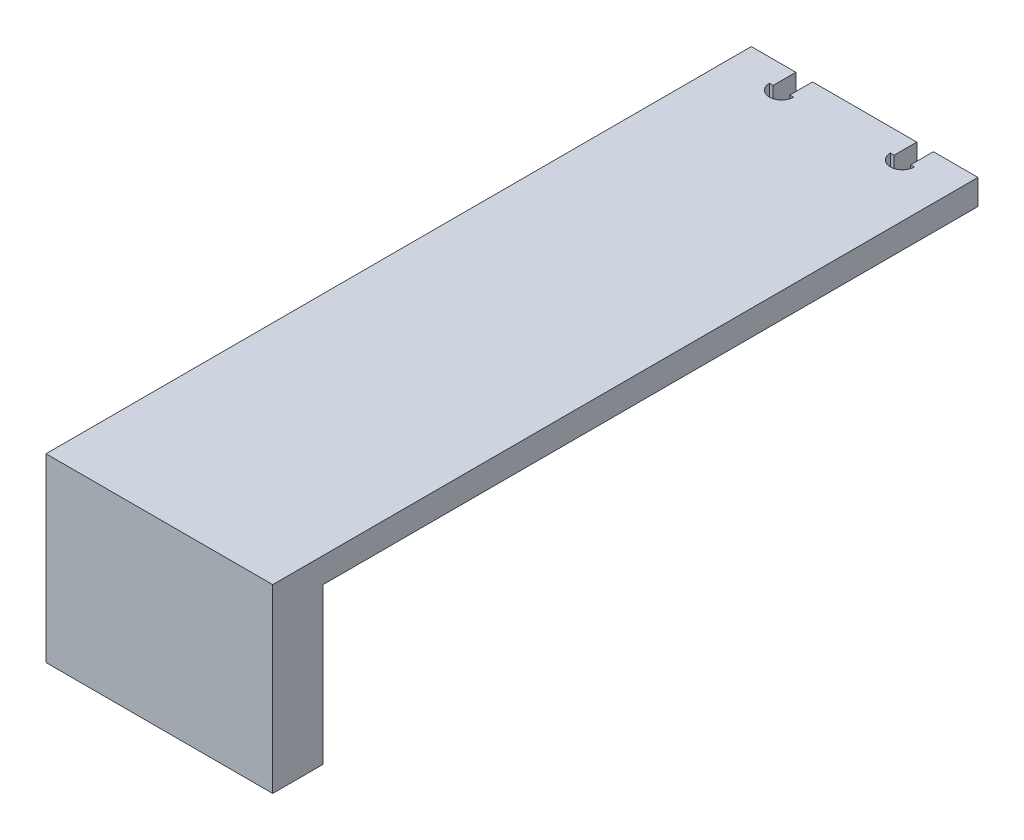
SolidWorks part; units mm, degrees
ref_plane "Front Plane" through (0, 0, 0) normal (0, 0, 1) x (1, 0, 0)
ref_plane "Top Plane" through (0, 0, 0) normal (0, 1, 0) x (1, 0, 0)
ref_plane "Right Plane" through (0, 0, 0) normal (1, 0, 0) x (0, 0, -1)
sketch "Sketch2" plane through (0, 0, 0) normal (0, 1, 0) x (1, 0, 0)
  line L0 (0, 65) -> (-12, 65) construction
  line L1 (-76.785, 65) -> (76.785, 65)
  line L2 (-76.785, 65) -> (-76.785, -65)
  line L3 (-76.785, -65) -> (76.785, -65)
  line L4 (76.785, 65) -> (76.785, -65)
  line L5 (-76.785, 65) -> (76.785, -65) construction
  line L6 (-76.785, -65) -> (76.785, 65) construction
  line L7 (-12, 65) -> (-13.65, 65)
  line L8 (-13.65, 65) -> (-13.65, 60.5)
  line L9 (-13.65, 60.5) -> (-14.4, 60.5)
  line L10 (-9.6, 60.5) -> (-10.35, 60.5)
  line L11 (-10.35, 60.5) -> (-10.35, 65)
  line L12 (-10.35, 65) -> (-13.65, 65)
  line L13 (0, 0) -> (0, 65) construction
  line L14 (10.35, 65) -> (13.65, 65)
  line L15 (10.35, 60.5) -> (10.35, 65)
  line L16 (9.6, 60.5) -> (10.35, 60.5)
  line L17 (13.65, 60.5) -> (14.4, 60.5)
  line L18 (13.65, 65) -> (13.65, 60.5)
  arc A0 (-14.4, 60.5) -> (-9.6, 60.5) centre (-12, 60.5) ccw
  arc A1 (14.4, 60.5) -> (9.6, 60.5) centre (12, 60.5) cw
  point P0 (0, 0)
  dimension "D7" = 4.5
  dimension "D1" = 65
  dimension "D2" = 153.57
  dimension "D3" = 12
  dimension "D4" = 1.65
  dimension "D5" = 1.65
  dimension "D6" = 0.75
extrude "Boss-Extrude1" add sketch "Sketch2" along normal mid plane 5 contours L17 A1 L16 L15 L1 L11 L10 A0 L9 L8 L2 L3 L4 L18
sketch "Sketch3" plane through (0, 2.5, 0) normal (0, 1, 0) x (1, 0, 0)
  line L0 (0, 65) -> (0, -65) construction
  line L1 (-10.35, 65) -> (10.35, 65) construction
  line L2 (-76.785, -65) -> (76.785, -65) construction
  circle A0 centre (0, 40) radius 15
  circle A1 centre (0, -44) radius 15
  circle A2 centre (0, 0) radius 18
  circle A3 centre (0, 0) radius 20.5
  circle A4 centre (0, 40) radius 17.5
  circle A5 centre (0, -44) radius 17.5
  point P16 (0, -43)
  dimension "D1" = 30
  dimension "D2" = 36
  dimension "D3" = 44
  dimension "D5" = 41
  dimension "D6" = 35
  dimension "D7" = 35
  dimension "D4" = 40
sketch "Sketch4" plane through (0, 2.5, 0) normal (0, 1, 0) x (1, 0, 0)
  line L0 (-22.5, 65) -> (-22.5, -65)
  line L1 (-22.5, -65) -> (22.5, -65) construction
  line L2 (22.5, -65) -> (22.5, 65)
  line L4 (-76.785, -65) -> (76.785, -65) construction
  line L5 (-22.5, 65) -> (22.5, 65)
  line L6 (22.5, -65) -> (-22.5, -65)
  line M14 (-13.65, 65) -> (-76.785, 65)
  line M15 (-76.785, 65) -> (-76.785, -65)
  line M16 (-76.785, -65) -> (76.785, -65)
  line M17 (76.785, -65) -> (76.785, 65)
  line M18 (76.785, 65) -> (13.65, 65)
  dimension "D1" = 45
  dimension "D2" = 22.5
  dimension "D3" = 130
extrude "Cut-Extrude1" cut sketch "Sketch4" against normal blind 120 contours L0 M14 M15 M16 | L2 M16 M17 M18
sketch "Sketch5" plane through (0, 0, 0) normal (1, 0, 0) x (0, 0, -1)
  line L1 (-65, 2.5) -> (-75, 2.5)
  line L2 (-65, 2.5) -> (-65, -33.4)
  line L3 (-65, -33.4) -> (-75, -33.4)
  line L4 (-75, 2.5) -> (-75, -33.4)
  line L5 (-70, -33.4) -> (-70, 2.5) construction
  line L6 (-65, -15.45) -> (-75, -15.45) construction
  point P316 (-70, -15.45)
  dimension "D1" = 35.9
  dimension "D2" = 10
extrude "Boss-Extrude2" add sketch "Sketch5" along normal mid plane 45
